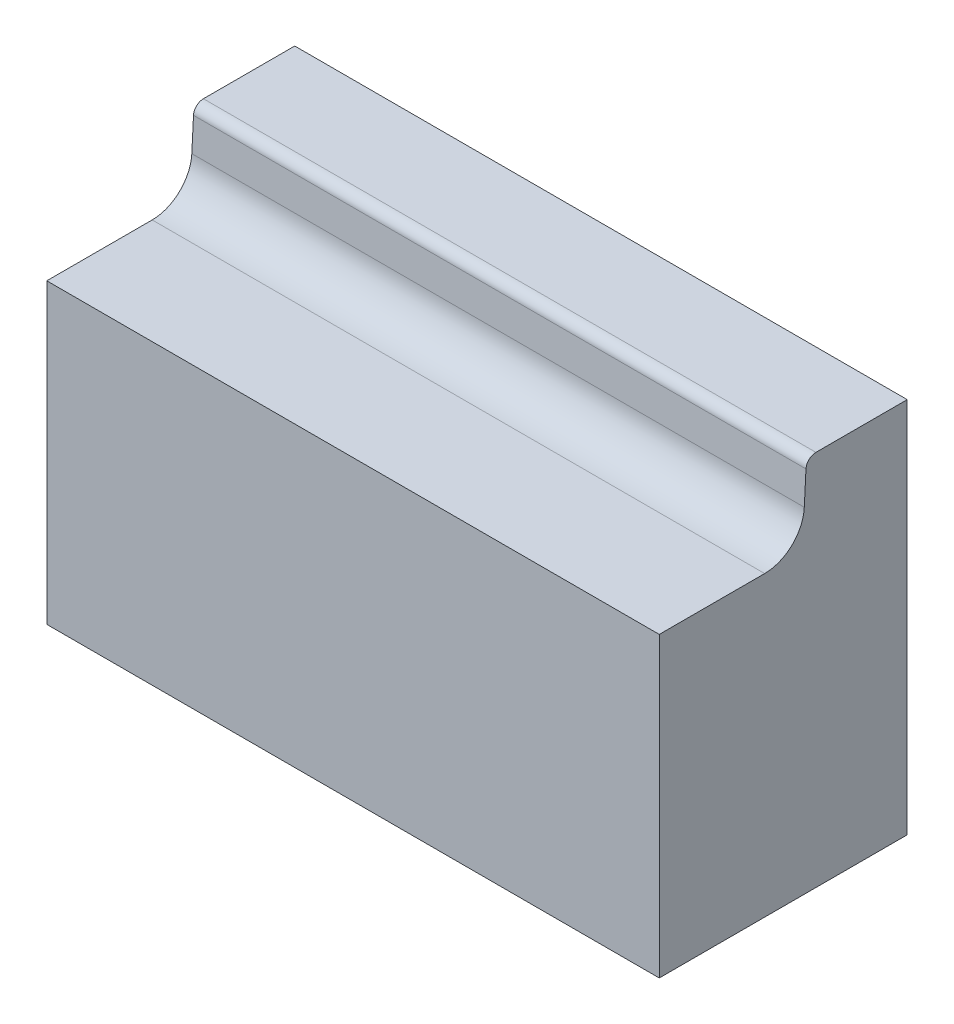
SolidWorks part; units mm, degrees
material "K110"
ref_plane "Front Plane" through (0, 0, 0) normal (0, 0, 1) x (1, 0, 0)
ref_plane "Top Plane" through (0, 0, 0) normal (0, 1, 0) x (1, 0, 0)
ref_plane "Right Plane" through (0, 0, 0) normal (1, 0, 0) x (0, 0, -1)
sketch "Sketch1" plane through (0, 0, 0) normal (0, 0, 1) x (1, 0, 0)
  line L1 (6.1065, -38) -> (67.8565, -38)
  line L2 (6.1065, -38) -> (6.1065, 0)
  line L3 (6.1065, 0) -> (67.8565, 0)
  line L4 (67.8565, -38) -> (67.8565, 0)
  dimension "D1" = 38
  dimension "D2" = 61.75
extrude "Boss-Extrude1" add sketch "Sketch1" along normal mid plane 25
sketch "Sketch2" plane through (67.8565, 0, 0) normal (1, 0, 0) x (0, 0, -1)
  line L0 (2.4945, 2.8958) -> (2.1222, -4.2093) construction
  line L1 (2.3428, 0) -> (2.1222, -4.2093)
  line L2 (-12.5, 0) -> (-12.5, -8)
  line L3 (-12.5, 0) -> (12.5, 0) construction
  line L4 (2.3428, 0) -> (-12.5, 0)
  line L5 (-12.5, -8) -> (-1.8724, -8)
  arc A0 (-1.8724, -8) -> (2.1222, -4.2093) centre (-1.8724, -4) ccw construction
  arc A1 (-1.8724, -8) -> (2.1222, -4.2093) centre (-1.8724, -4) ccw
extrude "Cut-Extrude1" cut sketch "Sketch2" against normal up to next
fillet "Fillet1" radius 1 1 edges at (36.9815, 0, -2.3428)
hole_wizard "M6 Tapped Hole1" positions "Sketch5" profile "Sketch4" tap size "M6" standard "ISO"
sketch "Sketch5" plane through (0, -38, 0) normal (0, -1, 0) x (-1, 0, 0)
  line L0 (-67.8565, 0) -> (-6.1065, 0) construction
  line L1 (-67.8565, -12.5) -> (-67.8565, 12.5) construction
  line L2 (-6.1065, -12.5) -> (-6.1065, 12.5) construction
  line L4 (-36.9815, 12.5) -> (-36.9815, -12.5) construction
  line L5 (-6.1065, 12.5) -> (-67.8565, 12.5) construction
  line L6 (-6.1065, -12.5) -> (-67.8565, -12.5) construction
  point P0 (-57.9815, 0)
  point P2 (-15.9815, 0)
  dimension "D1" = 42
sketch "Sketch4" plane through (57.9815, -38, 0) normal (1, 0, 0) x (0, 0, -1)
  line L0 (0, 0) -> (0, 18.5022)
  line L1 (0, 18.5022) -> (2.5, 17)
  line L2 (2.5, 17) -> (2.5, 0)
  line L5 (2.5, 0) -> (0, 0)
  line L10 (0, 18.5022) -> (-2.5, 17) construction
  line L11 (0, -6.35) -> (0, 107.95) construction
  dimension "Tap Drill Dia." = 5
  dimension "Tap Drill Depth" = 17
  dimension "Drill Angle" = 118
cosmetic thread "Hole Thread1"
cosmetic thread "Hole Thread2"
